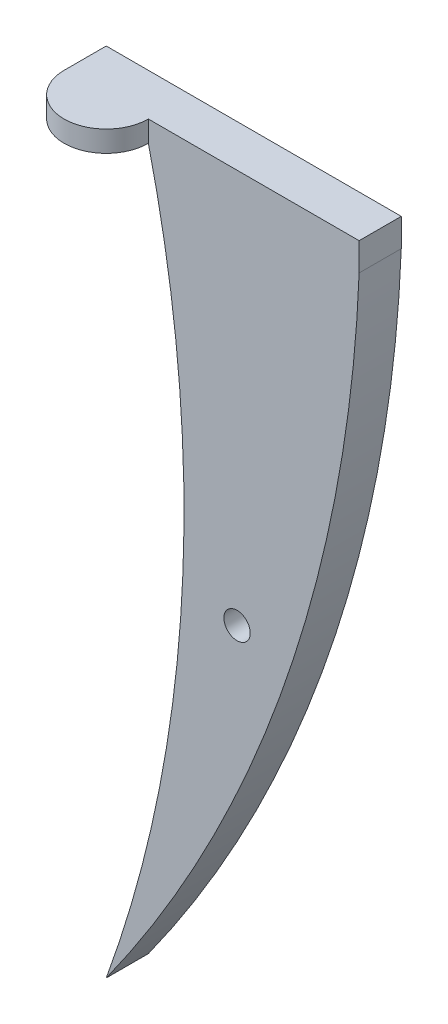
SolidWorks part; units mm, degrees
ref_plane "Front Plane" through (0, 0, 0) normal (0, 0, 1) x (1, 0, 0)
ref_plane "Top Plane" through (0, 0, 0) normal (0, 1, 0) x (1, 0, 0)
ref_plane "Right Plane" through (0, 0, 0) normal (1, 0, 0) x (0, 0, -1)
sketch "Sketch1" plane through (0, 0, 0) normal (0, 1, 0) x (1, 0, 0)
  line L1 (17.78, -2.54) -> (-17.78, -2.54)
  line L2 (17.78, -2.54) -> (17.78, 2.54)
  line L3 (17.78, 2.54) -> (-17.78, 2.54)
  line L4 (-17.78, -2.54) -> (-17.78, 2.54)
  line L5 (17.78, -2.54) -> (-17.78, 2.54) construction
  line L6 (17.78, 2.54) -> (-17.78, -2.54) construction
  point P0 (0, 0)
  dimension "D1" = 5.08
  dimension "D2" = 35.56
extrude "Boss-Extrude1" add sketch "Sketch1" along normal blind 92.202
sketch "Sketch4" plane through (0, 0, 2.54) normal (0, 0, 1) x (1, 0, 0)
  line L1 (-17.78, 92.202) -> (-7.62, 92.202)
  line L2 (-17.78, 92.202) -> (-17.78, 89.662)
  line L3 (-17.78, 89.662) -> (-7.62, 89.662)
  line L4 (-7.62, 92.202) -> (-7.62, 89.662)
  dimension "D1" = 2.54
  dimension "D2" = 10.16
extrude "Boss-Extrude4" add sketch "Sketch4" along normal blind 5.08
sketch "Sketch5" plane through (0, 92.202, 0) normal (0, 1, 0) x (1, 0, 0)
  line L0 (-7.62, -2.54) -> (-17.78, -2.54)
  arc A0 (-17.78, -2.54) -> (-7.62, -2.54) centre (-12.7, -2.54) ccw
  line M1 (-17.78, 2.54) -> (-17.78, -7.62)
  line M2 (-17.78, -7.62) -> (-7.62, -7.62)
  line M3 (-7.62, -7.62) -> (-7.62, -2.54)
extrude "Cut-Extrude1" cut sketch "Sketch5" against normal blind 2.54 contours A0 M1 M2 | A0 M2 M3
sketch "Sketch7" plane through (0, 0, 2.54) normal (0, 0, 1) x (1, 0, 0)
  line L0 (-7.62, 0) -> (-12.7, 0) construction
  line L1 (-7.62, 89.662) -> (17.78, 89.662)
  line L2 (-7.62, 89.662) -> (-17.78, 89.662)
  line L3 (-17.78, 89.662) -> (-17.78, 0)
  line L4 (-17.78, 0) -> (-12.7, 0)
  line L5 (-12.7, 0) -> (17.78, 0)
  line L6 (17.78, 0) -> (17.78, 89.662)
  line L7 (17.78, 92.202) -> (17.78, 0) construction
  arc A0 (-12.7, 0) -> (17.78, 88.8319) centre (-145.6702, 95.2698) ccw
  arc A1 (-12.7, 0) -> (-7.62, 89.662) centre (-159.4741, 53.2907) ccw
  line M5 (-17.78, 0) -> (17.78, 0)
  line M6 (17.78, 0) -> (17.78, 92.202)
  line M8 (-7.62, 89.662) -> (-17.78, 89.662)
  line M9 (-17.78, 89.662) -> (-17.78, 0)
extrude "Cut-Extrude3" cut sketch "Sketch7" against normal through all contours A1 M5 M8 M9 | A0 L5 M5 M6
sketch "Sketch9" plane through (0, 92.202, 0) normal (0, 1, 0) x (1, 0, 0)
  line L0 (-7.62, -2.54) -> (-12.7, -2.54) construction
  circle A0 centre (-12.7, -2.54) radius 1.5875 construction
  dimension "D1" = 3.175
sketch "Sketch11" plane through (0, 0, 2.54) normal (0, 0, 1) x (1, 0, 0)
  circle A2 centre (3.0699, 44.6786) radius 1.5875
  dimension "D1" = 3.175
extrude "Cut-Extrude5" cut sketch "Sketch11" against normal through all
equation "\"HEIGHT OF BASE PLATE\"= 2"
equation "\"THICK\"= .2"
equation "\"HOLE SIZE\"= .125"
